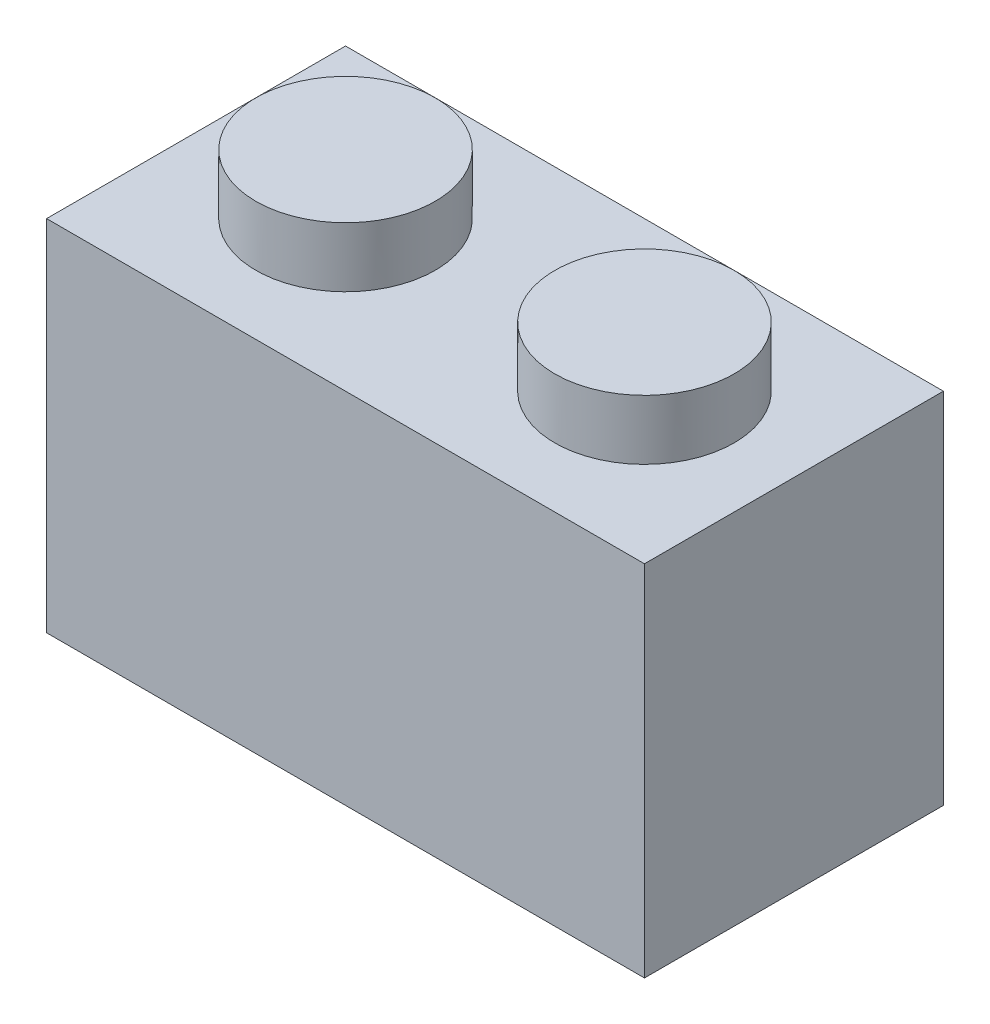
SolidWorks part; units mm, degrees
ref_plane "Front Plane" through (0, 0, 0) normal (0, 0, 1) x (1, 0, 0)
ref_plane "Top Plane" through (0, 0, 0) normal (0, 1, 0) x (1, 0, 0)
ref_plane "Right Plane" through (0, 0, 0) normal (1, 0, 0) x (0, 0, -1)
sketch "Sketch1" plane through (0, 0, 0) normal (0, 1, 0) x (1, 0, 0)
  line L1 (0, 0) -> (16, 0)
  line L2 (0, 0) -> (0, 8)
  line L3 (0, 8) -> (16, 8)
  line L4 (16, 0) -> (16, 8)
  dimension "D1" = 16
  dimension "D2" = 8
extrude "Boss-Extrude1" add sketch "Sketch1" along normal blind 9.6
sketch "Sketch2" plane through (0, 9.6, 0) normal (0, 1, 0) x (1, 0, 0)
  line L0 (8, 0) -> (8, 8) construction
  line L1 (0, 0) -> (16, 0) construction
  line L2 (16, 8) -> (0, 8) construction
  line L3 (16, 0) -> (16, 4) construction
  line L4 (16, 0) -> (16, 8) construction
  line L5 (16, 4) -> (12, 4) construction
  circle A0 centre (12, 4) radius 2.4
  dimension "D3" = 4.8
  dimension "D1" = 4
  dimension "D2" = 4
extrude "Boss-Extrude2" add sketch "Sketch2" along normal blind 1.6
pattern_linear "LPattern1" count 2 spacing 8 along (-1, 0, 0) count 4 spacing 8 along (0, 0, -1) of "Boss-Extrude2"
shell "Shell1" thickness 1.6
